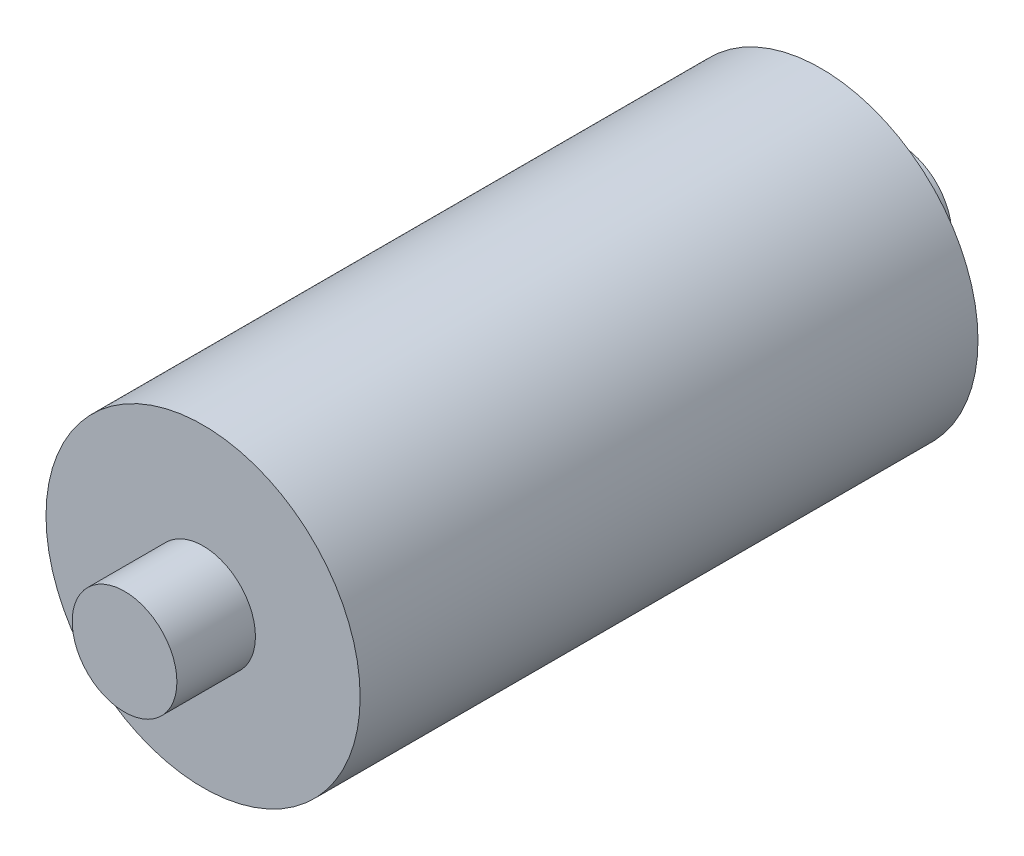
SolidWorks part; units mm, degrees
ref_plane "Front Plane" through (0, 0, 0) normal (0, 0, 1) x (1, 0, 0)
ref_plane "Top Plane" through (0, 0, 0) normal (0, 1, 0) x (1, 0, 0)
ref_plane "Right Plane" through (0, 0, 0) normal (1, 0, 0) x (0, 0, -1)
sketch "Sketch1" plane through (0, 0, 0) normal (0, 0, 1) x (1, 0, 0)
  circle A0 centre (0, 0) radius 15
  dimension "D1" = 30
extrude "Boss-Extrude1" add sketch "Sketch1" along normal mid plane 59
sketch "Sketch2" plane through (0, 0, 29.5) normal (0, 0, 1) x (1, 0, 0)
  circle A0 centre (0, 0) radius 5
  dimension "D1" = 10
extrude "Boss-Extrude2" add sketch "Sketch2" along normal mid plane 15
sketch "Sketch3" plane through (0, 0, -29.5) normal (0, 0, -1) x (-1, 0, 0)
  circle A0 centre (0, 0) radius 5
extrude "Boss-Extrude3" add sketch "Sketch3" along normal mid plane 15
